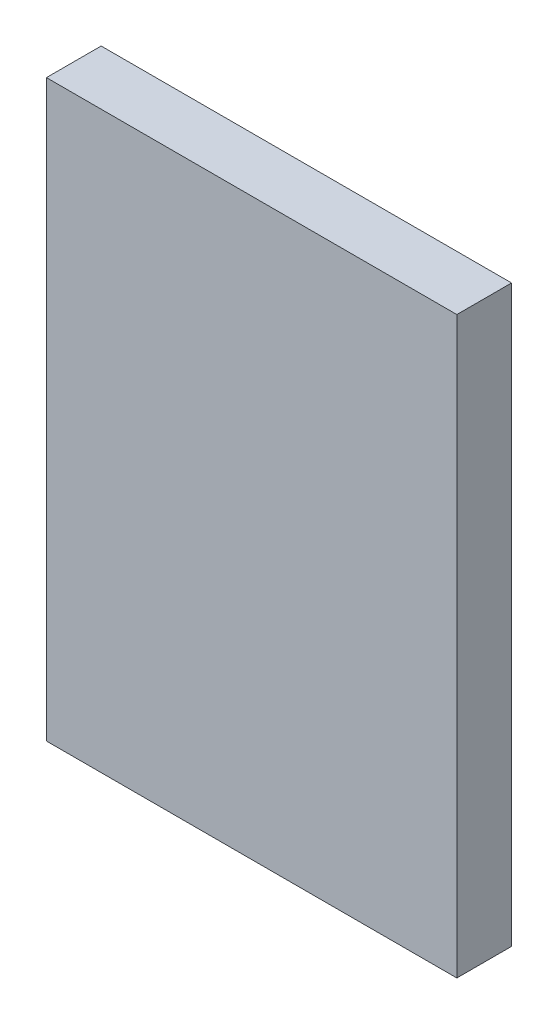
SolidWorks part; units mm, degrees
ref_plane "Alzado" through (0, 0, 0) normal (0, 0, 1) x (1, 0, 0)
ref_plane "Planta" through (0, 0, 0) normal (0, 1, 0) x (1, 0, 0)
ref_plane "Vista lateral" through (0, 0, 0) normal (1, 0, 0) x (0, 0, -1)
sketch "Croquis1" plane through (0, 0, 0) normal (0, 0, 1) x (1, 0, 0)
  line L1 (0, 0) -> (30, 0)
  line L2 (0, 0) -> (0, -42)
  line L3 (0, -42) -> (30, -42)
  line L4 (30, 0) -> (30, -42)
  dimension "D1" = 42
  dimension "D2" = 30
extrude "Saliente-Extruir1" add sketch "Croquis1" along normal blind 4
